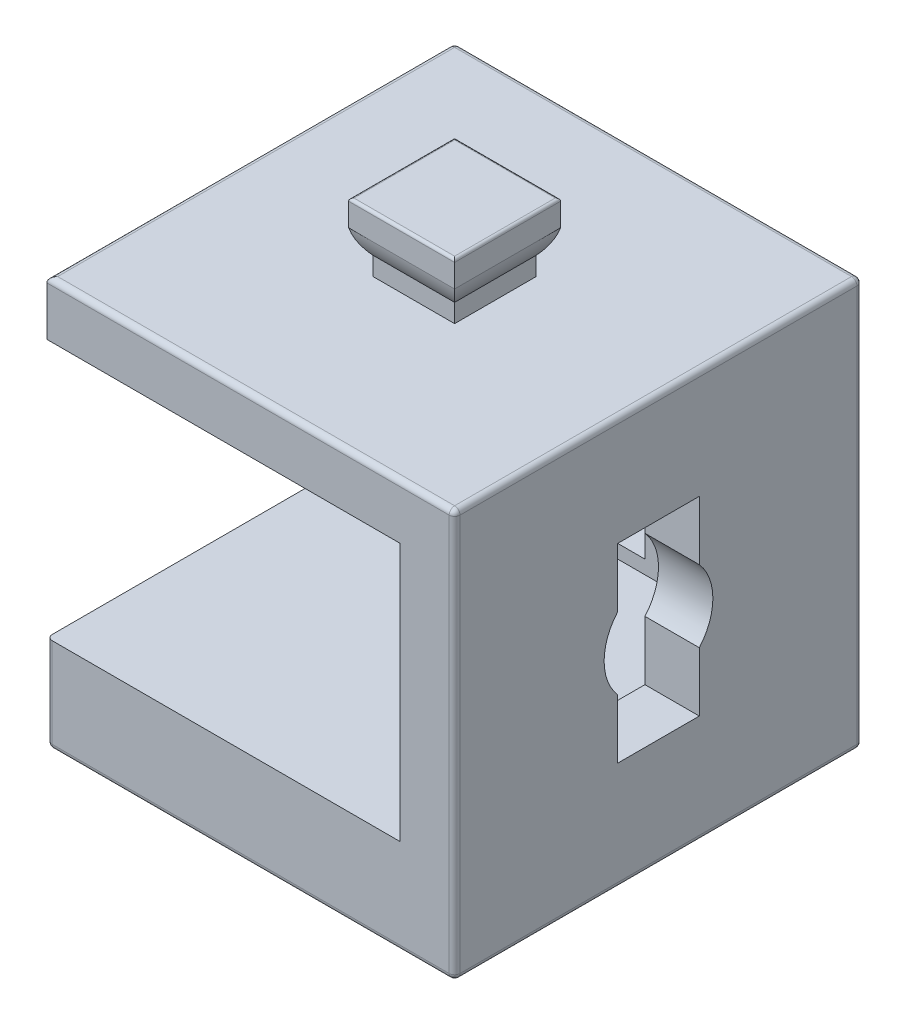
SolidWorks part; units mm, degrees
ref_plane "前视基准面" through (0, 0, 0) normal (0, 0, 1) x (1, 0, 0)
ref_plane "上视基准面" through (0, 0, 0) normal (0, 1, 0) x (1, 0, 0)
ref_plane "右视基准面" through (0, 0, 0) normal (1, 0, 0) x (0, 0, -1)
sketch "草图1" plane through (0, 0, 0) normal (0, 0, 1) x (1, 0, 0)
  line L1 (-7.5, 0) -> (7.5, 0)
  line L2 (-7.5, 0) -> (-7.5, 15)
  line L3 (-7.5, 15) -> (7.5, 15)
  line L4 (7.5, 0) -> (7.5, 15)
extrude "凸台-拉伸1" add sketch "草图1" against normal blind 15
sketch "草图2" plane through (-7.5, 0, 0) normal (-1, 0, 0) x (0, 0, 1)
  line L0 (0, 15) -> (0, 0) construction
  line L1 (-13, 3.5) -> (0, 3.5)
  line L2 (-13, 3.5) -> (-13, 13)
  line L3 (-13, 13) -> (0, 13)
  line L4 (0, 3.5) -> (0, 13)
extrude "切除-拉伸1" cut sketch "草图2" against normal blind 13
sketch "草图4" plane through (0, 0, 0) normal (0, 0, 1) x (1, 0, 0)
  line L2 (-1.5, 15.6771) -> (1.5, 15.6771)
  line L5 (-1.95, 17.5) -> (1.95, 17.5)
  line L6 (-1.95, 17.5) -> (-1.95, 16.5556)
  line L7 (1.95, 17.5) -> (1.95, 16.5556)
  arc A1 (-1.95, 16.5556) -> (-1.5, 15.6771) centre (0, 17) ccw
  arc A2 (1.5, 15.6771) -> (1.95, 16.5556) centre (0, 17) ccw
extrude "凸台-拉伸2" add sketch "草图4" against normal blind 6 from offset 4.5 offset against normal yes
sketch "草图5" plane through (0, 15, 0) normal (0, 1, 0) x (-1, 0, 0)
  line L1 (1.5, -9) -> (-1.5, -9)
  line L2 (1.5, -9) -> (1.5, -6)
  line L3 (1.5, -6) -> (-1.5, -6)
  line L4 (-1.5, -9) -> (-1.5, -6)
extrude "凸台-拉伸3" add sketch "草图5" along normal blind 1
sketch "草图6" plane through (0, 0, -15) normal (0, 0, -1) x (-1, 0, 0)
  line L0 (-1.5, 6.1771) -> (-1.5, 4)
  line L1 (-1.5, 11) -> (1.5, 11)
  line L2 (-1.5, 11) -> (-1.5, 8.8229)
  line L3 (-1.5, 4) -> (1.5, 4)
  line L4 (1.5, 11) -> (1.5, 8.8229)
  line L5 (1.5, 6.1771) -> (1.5, 4)
  arc A0 (-1.5, 8.8229) -> (-1.5, 6.1771) centre (0, 7.5) ccw
  arc A1 (1.5, 6.1771) -> (1.5, 8.8229) centre (0, 7.5) ccw
extrude "切除-拉伸3" cut sketch "草图6" against normal up to next
sketch "草图7" plane through (7.5, 0, 0) normal (1, 0, 0) x (0, 0, -1)
  line L0 (6, 6.1771) -> (6, 4)
  line L1 (6, 11) -> (9, 11)
  line L2 (6, 11) -> (6, 8.8229)
  line L3 (6, 4) -> (9, 4)
  line L4 (9, 11) -> (9, 8.8229)
  line L5 (9, 6.1771) -> (9, 4)
  arc A0 (6, 8.8229) -> (6, 6.1771) centre (7.5, 7.5) ccw
  arc A1 (9, 6.1771) -> (9, 8.8229) centre (7.5, 7.5) ccw
extrude "切除-拉伸4" cut sketch "草图7" against normal up to next
sketch "草图8" plane through (0, 0, 0) normal (1, 0, 0) x (0, 0, -1)
  line L2 (5.55, 17.5) -> (5.55, 16.5556)
  line L3 (7.5, 18.1799) -> (7.5, 15.0835) construction
  line L4 (6, 15.6771) -> (4.5, 15.6771)
  line L7 (6, 15.6771) -> (4.5, 15.6771) construction
  line L8 (4.5, 15.6771) -> (4.5, 17.5)
  line L9 (4.5, 17.5) -> (5.55, 17.5)
  line L10 (10.5, 17.5) -> (9.45, 17.5)
  line L11 (10.5, 15.6771) -> (10.5, 17.5)
  line L12 (9, 15.6771) -> (10.5, 15.6771)
  line L13 (9.45, 17.5) -> (9.45, 16.5556)
  arc A0 (5.55, 16.5556) -> (6, 15.6771) centre (7.5, 17) ccw
  arc A1 (9.45, 16.5556) -> (9, 15.6771) centre (7.5, 17) cw
extrude "切除-拉伸5" cut sketch "草图8" against normal up to next and the other way up to next
fillet "圆角1" radius 0.1 4 edges at (0, 17.5, -5.55) (-1.95, 17.5, -7.5) (0, 17.5, -9.45) (1.95, 17.5, -7.5)
fillet "圆角2" radius 0.2 12 edges at (0, 0, 0) (7.5, 0, -7.5) (0, 0, -15) (-7.5, 0, -7.5) (7.5, 7.5, -15) (0, 15, -15) (-7.5, 15, -7.5) (-7.5, 7.5, -15) (-7.5, 1.75, 0) (7.5, 7.5, 0) (7.5, 15, -7.5) (0, 15, 0)
sketch "草图9" plane through (0, 0, 0) normal (1, 0, 0) x (0, 0, -1)
  line L0 (7.5, 0) -> (7.5, -2) construction
  line L1 (14.8, 0) -> (0.2, 0) construction
  line L2 (7.5, -2) -> (7.5, -2.5) construction
  line L3 (6, 0) -> (9, 0)
  line L4 (9, 0) -> (9, -0.6771)
  line L5 (5.55, -2.5) -> (9.45, -2.5)
  line L6 (9.45, -2.5) -> (9.45, -1.5556)
  line L7 (5.55, -2.5) -> (5.55, -1.5556)
  line L8 (6, 0) -> (6, -0.6771)
  arc A0 (9.45, -1.5556) -> (9, -0.6771) centre (7.5, -2) ccw
  arc A1 (5.55, -1.5556) -> (6, -0.6771) centre (7.5, -2) cw
  dimension "D5" = 2
  dimension "D1" = 2
  dimension "D2" = 0.5
  dimension "D3" = 1.5
  dimension "D4" = 1.95
extrude "凸台-拉伸4" add sketch "草图9" along normal blind 3 and the other way blind 3
sketch "草图10" plane through (0, 0, 0) normal (0, 0, 1) x (1, 0, 0)
  line L0 (0, 0) -> (0, -2) construction
  line L1 (0, -2) -> (0, -2.5) construction
  line L2 (-3, -2.5) -> (3, -2.5) construction
  line L4 (-1.95, -2.5) -> (-1.95, -1.5556)
  line L5 (-3, 0) -> (3, 0) construction
  line L6 (1.5, 0) -> (1.5, -0.6771)
  line L7 (-1.5, 0) -> (-1.5, -0.6771)
  line L8 (1.95, -2.5) -> (1.95, -1.5556)
  line L9 (1.95, -2.5) -> (3, -2.5)
  line L10 (-3, 0) -> (-1.5, 0)
  line L11 (-3, 0) -> (-3, -2.5)
  line L12 (-3, -2.5) -> (-1.95, -2.5)
  line L13 (3, 0) -> (3, -2.5)
  line L14 (1.5, 0) -> (3, 0)
  arc A0 (1.95, -1.5556) -> (1.5, -0.6771) centre (0, -2) ccw
  arc A1 (-1.95, -1.5556) -> (-1.5, -0.6771) centre (0, -2) cw
  dimension "D1" = 2
  dimension "D2" = 1.5
  dimension "D3" = 1.95
extrude "切除-拉伸6" cut sketch "草图10" against normal blind 15
fillet "圆角3" radius 0.1 4 edges at (1.95, -2.5, -7.5) (0, -2.5, -9.45) (-1.95, -2.5, -7.5) (0, -2.5, -5.55)
